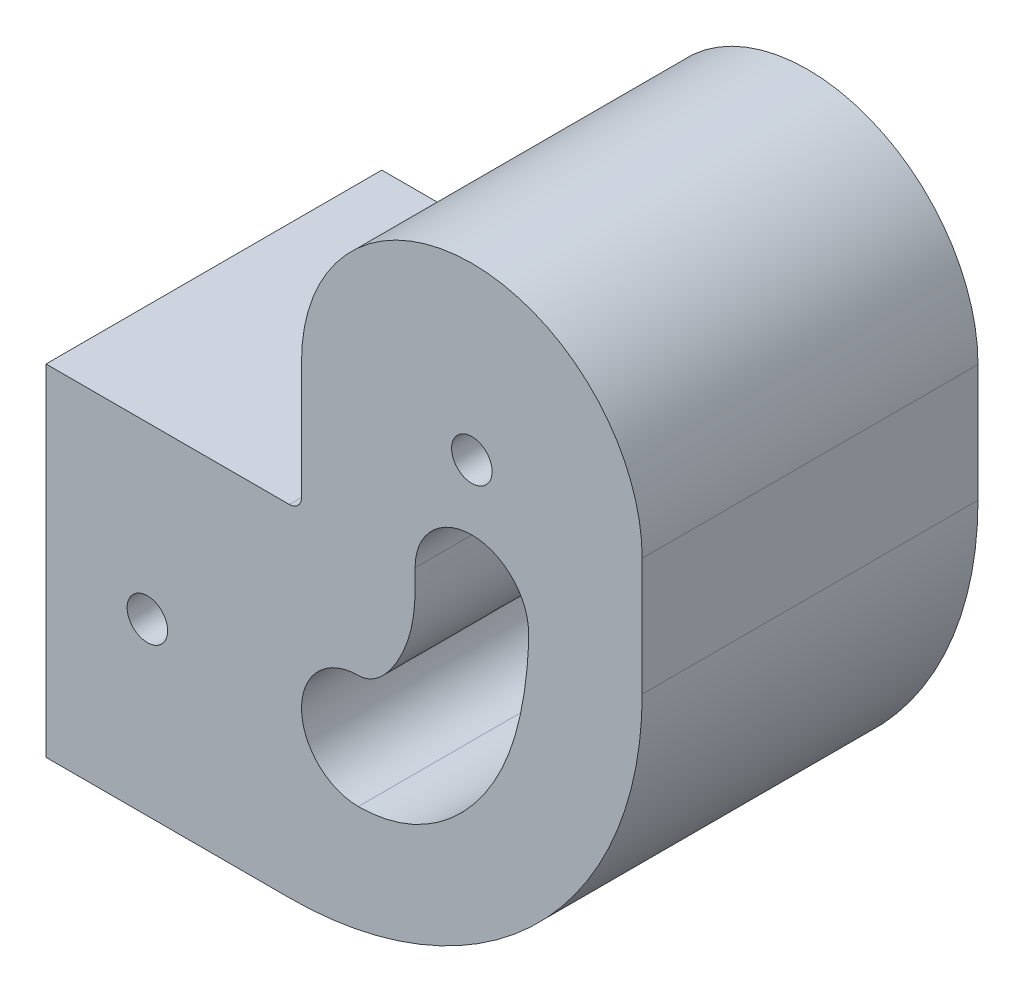
SolidWorks part; units mm, degrees
ref_plane "Front Plane" through (0, 0, 0) normal (0, 0, 1) x (1, 0, 0)
ref_plane "Top Plane" through (0, 0, 0) normal (0, 1, 0) x (1, 0, 0)
ref_plane "Right Plane" through (0, 0, 0) normal (1, 0, 0) x (0, 0, -1)
sketch "Sketch1" plane through (0, 0, 0) normal (0, 0, 1) x (1, 0, 0)
  line L0 (8.1255, 31.7481) -> (-21.8745, 31.7481)
  line L1 (-21.8745, 31.7481) -> (-21.8745, -10.2519)
  line L2 (-21.8745, -10.2519) -> (8.1255, -10.2519)
  line L3 (9.6255, 47.7481) -> (9.6255, 33.2481)
  line L5 (51.6255, 47.7481) -> (51.6255, 33.2481)
  line L6 (9.6255, 47.7481) -> (51.6255, 47.7481) construction
  arc A0 (8.1255, 31.7481) -> (9.6255, 33.2481) centre (8.1255, 33.2481) ccw
  arc A1 (8.1255, -10.2519) -> (51.6255, 33.2481) centre (8.1255, 33.2481) ccw
  arc A2 (9.6255, 47.7481) -> (51.6255, 47.7481) centre (30.6255, 47.7481) cw
  circle A4 centre (-9.3745, 10.7481) radius 2.5
  circle A5 centre (30.6255, 47.7481) radius 2.5
  dimension "D1" = 5
  dimension "D6" = 5
  dimension "D2" = 12.5
  dimension "D3" = 42
  dimension "D4" = 21
  dimension "D5" = 37
  dimension "D7" = 40
  dimension "D8" = 16
  dimension "D9" = 30
  dimension "D10" = 30
extrude "Boss-Extrude1" add sketch "Sketch1" along normal blind 41.4
sketch "Sketch2" plane through (-21.8745, 0, 0) normal (-1, 0, 0) x (0, 0, 1)
  line L1 (7.7, 23.7481) -> (33.7, 23.7481)
  line L2 (7.7, 23.7481) -> (7.7, -2.2519)
  line L3 (7.7, -2.2519) -> (33.7, -2.2519)
  line L4 (33.7, 23.7481) -> (33.7, -2.2519)
  line L5 (41.4, -10.2519) -> (0, -10.2519) construction
  line L6 (0, 31.7481) -> (0, -10.2519) construction
  dimension "D1" = 26
  dimension "D2" = 26
  dimension "D3" = 8
  dimension "D4" = 7.7
extrude "Cut-Extrude1" cut sketch "Sketch2" against normal blind 31
sketch "Sketch3" plane through (0, 0, 41.4) normal (0, 0, 1) x (1, 0, 0)
  line L0 (-21.8745, 31.7481) -> (-21.8745, -10.2519) construction
  line L1 (-21.8745, 10.7481) -> (16.6255, 10.7481) construction
  arc A2 (23.6255, 32.7481) -> (37.6255, 32.7481) centre (30.6255, 32.7481) cw
  arc A3 (16.6255, 17.7481) -> (16.6255, 3.7481) centre (16.6255, 10.7481) ccw
  arc A4 (51.6255, 47.7481) -> (9.6255, 47.7481) centre (30.6255, 47.7481) ccw construction
  circle A9 centre (30.6255, 47.7481) radius 2.5 construction
  spline S0 degree 3 poles (16.6255, 17.7481) (19.4618, 17.7481) (23.8826, 24.8264) (23.6255, 30.3988) (23.6255, 32.7481) knots 0 0 0 0 0.571663 1 1 1 1
  spline S1 degree 3 poles (16.6255, 3.7481) (24.9405, 3.7481) (36.1711, 14.1203) (37.6255, 29.3528) (37.6255, 32.7481) knots 0 0 0 0 0.619735 1 1 1 1
  point P12 (-21.8745, 10.7481)
  point P16 (30.6255, 68.7481)
  dimension "D1" = 7
  dimension "D2" = 38.5
  dimension "D3" = 15
  dimension "D4" = 7
extrude "Cut-Extrude4" cut sketch "Sketch3" against normal up to surface (41.4 mm away) up to face at (13.0405, 27.0831, 0)
sketch "Sketch4" plane through (0, 0, 33.7) normal (0, 0, -1) x (-1, 0, 0)
  circle A0 centre (9.3745, 10.7481) radius 2.5
extrude "Boss-Extrude2" add sketch "Sketch4" against normal blind 0.4
